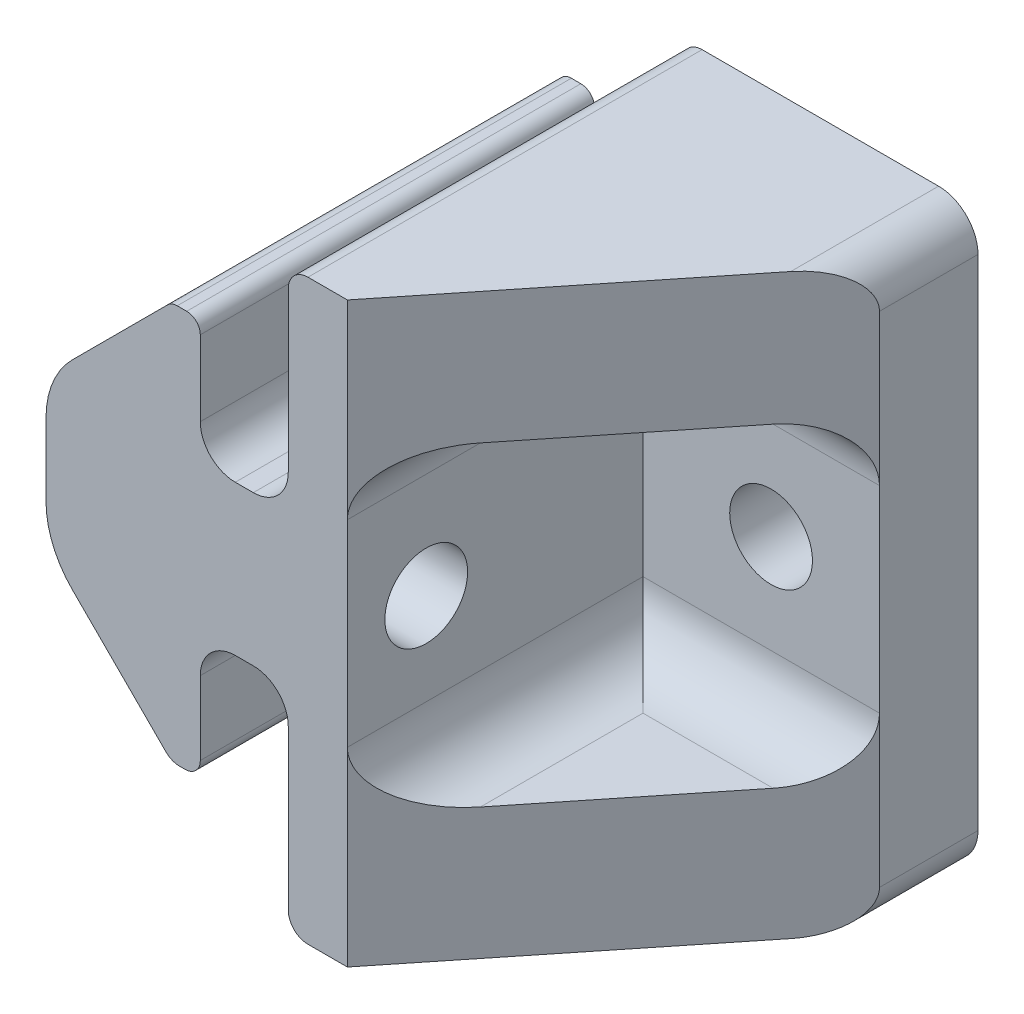
SolidWorks part; units mm, degrees
ref_plane "Front Plane" through (0, 0, 0) normal (0, 0, 1) x (1, 0, 0)
ref_plane "Top Plane" through (0, 0, 0) normal (0, 1, 0) x (1, 0, 0)
ref_plane "Right Plane" through (0, 0, 0) normal (1, 0, 0) x (0, 0, -1)
sketch "Sketch1" plane through (0, 0, 0) normal (0, 0, 1) x (1, 0, 0)
  line L0 (38.3, 9.8814) -> (38.3, 10.7456)
  line L1 (38.3, 27.3535) -> (38.3, 28.2156)
  line L2 (39.3, 33.711) -> (41.3, 33.711)
  line L3 (33.836, 28.448) -> (33.836, 24.6302)
  line L6 (53.3, 29.711) -> (53.3, 31.711)
  line L7 (51.3, 33.711) -> (41.3, 33.711)
  line L8 (40.3, 4.3943) -> (51.3, 4.3943)
  line L9 (40.3, 4.3943) -> (39.3, 4.3943)
  line L10 (53.3, 29.711) -> (53.3, 6.3943)
  line L327 (33.836, 28.448) -> (33.836, 24.6302)
  line L328 (35.6108, 22.8554) -> (36.5252, 22.8554)
  line L329 (38.3, 24.6302) -> (38.3, 27.3535)
  line L330 (38.3, 28.2156) -> (38.3, 32.711)
  line L426 (38.3, 5.3943) -> (38.3, 9.8814)
  line L427 (38.3, 10.7456) -> (38.3, 13.4698)
  line L428 (36.5252, 15.2446) -> (35.6108, 15.2446)
  line L429 (33.836, 13.4698) -> (33.836, 9.7387)
  line L430 (33.0603, 8.963) -> (32.7869, 8.963)
  line L431 (32.0904, 9.2515) -> (27.339, 14.0029)
  line L432 (26.0064, 17.2201) -> (26.0064, 20.8799)
  line L433 (27.339, 24.0971) -> (32.1771, 28.9352)
  line L434 (32.6643, 29.137) -> (33.147, 29.137)
  arc A0 (53.3, 6.3943) -> (51.3, 4.3943) centre (51.3, 6.3943) cw
  arc A1 (53.3, 31.711) -> (51.3, 33.711) centre (51.3, 31.711) ccw
  arc A2 (39.3, 33.711) -> (38.3, 32.711) centre (39.3, 32.711) ccw
  arc A3 (39.3, 4.3943) -> (38.3, 5.3943) centre (39.3, 5.3943) cw
  arc A360 (33.836, 28.448) -> (33.147, 29.137) centre (33.147, 28.448) ccw
  arc A361 (33.836, 24.6302) -> (35.6108, 22.8554) centre (35.6108, 24.6302) ccw
  arc A362 (36.5252, 22.8554) -> (38.3, 24.6302) centre (36.5252, 24.6302) ccw
  arc A473 (38.3, 13.4698) -> (36.5252, 15.2446) centre (36.5252, 13.4698) ccw
  arc A474 (35.6108, 15.2446) -> (33.836, 13.4698) centre (35.6108, 13.4698) ccw
  arc A475 (33.0603, 8.963) -> (33.836, 9.7387) centre (33.0603, 9.7387) ccw
  arc A476 (32.0904, 9.2515) -> (32.7869, 8.963) centre (32.7869, 9.9481) ccw
  arc A477 (26.0064, 17.2201) -> (27.339, 14.0029) centre (30.5562, 17.2201) ccw
  arc A478 (27.339, 24.0971) -> (26.0064, 20.8799) centre (30.5562, 20.8799) ccw
  arc A479 (32.6643, 29.137) -> (32.1771, 28.9352) centre (32.6643, 28.448) ccw
  dimension "D1" = 2
  dimension "D2" = 2
  dimension "D3" = 1
extrude "Boss-Extrude1" add sketch "Sketch1" against normal blind 20
sketch "Sketch6" plane through (0, 0, 0) normal (0, 0, 1) x (1, 0, 0)
  line L0 (53.3, 19.0527) -> (53.3, 27.0527)
  line L1 (53.3, 31.711) -> (53.3, 6.3943) construction
  line L2 (53.3, 19.0527) -> (53.3, 11.0527)
  line L4 (41.3, 13.4698) -> (41.3, 27.0527)
  line L5 (41.3, 5.3943) -> (41.3, 13.4698)
  line L6 (41.3, 11.0527) -> (41.3, 13.4698)
  line L7 (53.3, 27.0527) -> (41.3, 27.0527)
  line L8 (53.3, 11.0527) -> (41.3, 11.0527)
  dimension "D1" = 3
extrude "Cut-Extrude5" cut sketch "Sketch6" against normal offset from surface (15 mm away) 5 up to face at (36.5451, 19.0556, -20)
sketch "Sketch3" plane through (41.3, 0, 0) normal (1, 0, 0) x (0, 0, -1)
  circle A0 centre (4, 18.711) radius 2.1
extrude "Cut-Extrude2" cut sketch "Sketch3" against normal through all
sketch "Sketch5" plane through (0, 0, -20) normal (0, 0, -1) x (-1, 0, 0)
  circle A0 centre (-47.8, 19.0527) radius 2.1
extrude "Cut-Extrude4" cut sketch "Sketch5" against normal through all
sketch "Sketch7" plane through (0, 4.3943, 0) normal (0, -1, 0) x (1, 0, 0)
  line L4 (41.3, 0) -> (53.3, -15)
  line L5 (53.3, -15) -> (53.3, 0) construction
  line L6 (41.3, 0) -> (53.3, 0) construction
  line L7 (53.3, -15) -> (53.3, 0)
  line L8 (41.3, 0) -> (53.3, 0)
extrude "Cut-Extrude6" cut sketch "Sketch7" against normal through all
fillet "Fillet1" radius 3 4 edges at (41.3, 11.0527, -7.5) (47.3, 11.0527, -15) (47.3, 27.0527, -15) (41.3, 27.0527, -7.5)
